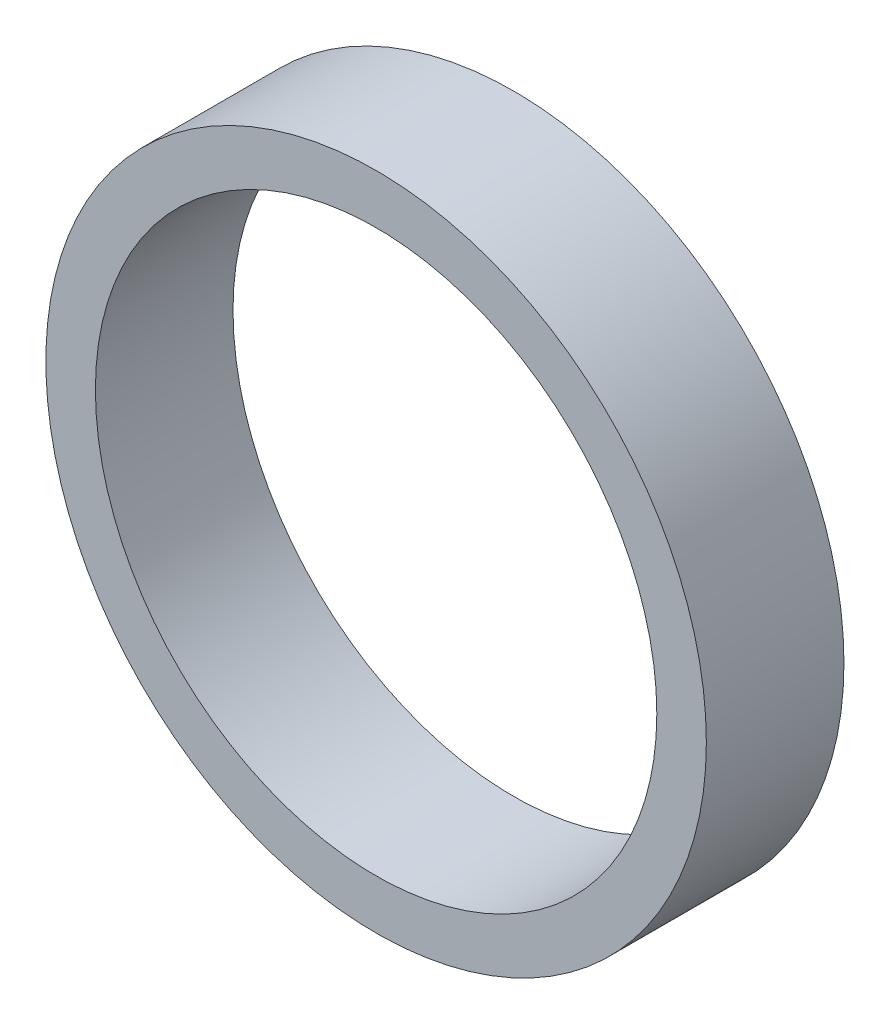
SolidWorks part; units mm, degrees
material "AISI Type 316L stainless steel"
ref_plane "Front Plane" through (0, 0, 0) normal (0, 0, 1) x (1, 0, 0)
ref_plane "Top Plane" through (0, 0, 0) normal (0, 1, 0) x (1, 0, 0)
ref_plane "Right Plane" through (0, 0, 0) normal (1, 0, 0) x (0, 0, -1)
sketch "Sketch1" plane through (0, 0, 0) normal (0, 0, 1) x (1, 0, 0)
  circle A0 centre (0, 0) radius 5.1
  circle A1 centre (0, 0) radius 6
  dimension "D1" = 10.2
  dimension "D2" = 12
extrude "Boss-Extrude1" add sketch "Sketch1" along normal blind 2.5
